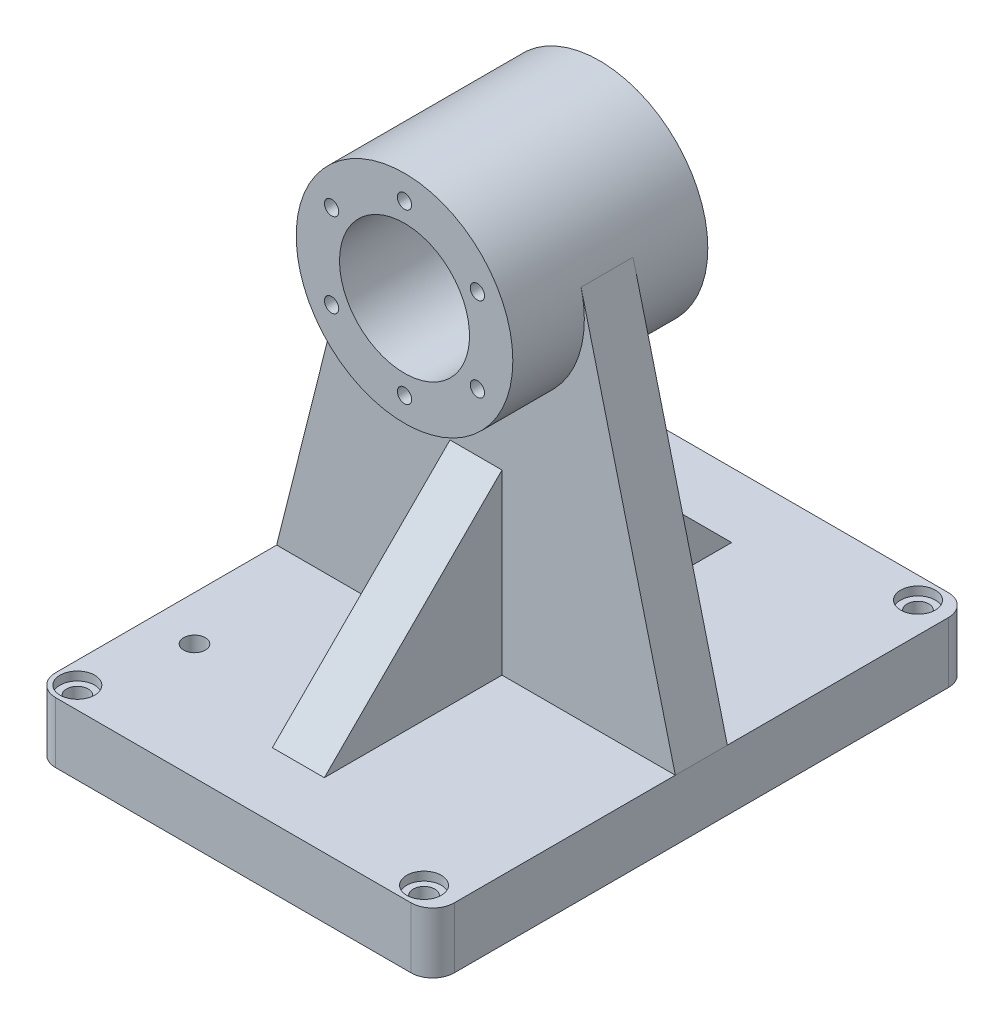
SolidWorks part; units mm, degrees
ref_plane "정면" through (0, 0, 0) normal (0, 0, 1) x (1, 0, 0)
ref_plane "윗면" through (0, 0, 0) normal (0, 1, 0) x (1, 0, 0)
ref_plane "우측면" through (0, 0, 0) normal (1, 0, 0) x (0, 0, -1)
sketch "스케치1" plane through (0, 0, 0) normal (0, 0, 1) x (1, 0, 0)
  circle A0 centre (0, 0.5754) radius 25
  circle A1 centre (0, 0.5754) radius 15
  point P3 (0, 0)
  dimension "D1" = 50
  dimension "D2" = 30
extrude "보스-돌출1" add sketch "스케치1" along normal mid plane 45
sketch "스케치2" plane through (0, 0, 0) normal (0, 0, 1) x (1, 0, 0)
  line L1 (-46, -80) -> (46, -80)
  line L2 (-46, -80) -> (-46, -94)
  line L3 (-46, -94) -> (46, -94)
  line L4 (46, -80) -> (46, -94)
  point P4 (0, -80)
  dimension "D1" = 14
  dimension "D2" = 92
  dimension "D3" = 80
extrude "보스-돌출2" add sketch "스케치2" along normal mid plane 124 separate body contours L1 L4 L3 L2
sketch "스케치4" plane through (0, 0, 0) normal (0, 0, 1) x (1, 0, 0)
  line L0 (-24.2478, 6.6616) -> (-46, -80)
  line L1 (-46, -80) -> (46, -80)
  line L2 (46, -80) -> (24.2478, 6.6616)
  circle A0 centre (0, 0.5754) radius 25 construction
  arc A1 (-24.2478, 6.6616) -> (24.2478, 6.6616) centre (0, 0.5754) ccw
extrude "보스-돌출3" add sketch "스케치4" along normal mid plane 12
sketch "스케치5" plane through (0, 0, 0) normal (1, 0, 0) x (0, 0, -1)
  line L0 (-47, -80) -> (-6, -39)
  line L1 (-62, -80) -> (-6, -80) construction
  line L2 (-6, -80) -> (-6, 6.6616) construction
  dimension "D1" = 15
  dimension "D2" = 45
rib "보강대1" sketch "스케치5" sketch "스케치5" thickness 12 extrusion direction parallel to sketch draft on no parameters "D1"=12
mirror "대칭 복사1" about plane through (0, 0, 0) normal (0, 0, 1) of "보강대1"
fillet "필렛1" radius 5 4 edges at (-46, -87, -62) (46, -87, -62) (46, -87, 62) (-46, -87, 62)
hole_wizard "M4 소켓 머리 캡 나사용 카운터보어2" positions "3D스케치2" profile "스케치9" counterbore size "M4" standard "KS" end condition through all
sketch3d "3D스케치2"
  line L0 (-41, -94, 57) -> (-41, -80, 57) construction
  point P0 (-41, -80, 57)
sketch "스케치9" plane through (-41, -80, 57) normal (1, 0, 0) x (0, 0, 1)
  line L0 (0, 0) -> (0, 14)
  line L1 (0, 14) -> (2.5, 14)
  line L3 (2.5, 14) -> (2.5, 2)
  line L4 (2.5, 2) -> (4, 2)
  line L5 (4, 2) -> (4, 0)
  line L7 (4, 0) -> (0, 0)
  line L11 (0, -6.35) -> (0, 107.95) construction
  dimension "관통 구멍 지름" = 5
  dimension "관통 구멍 깊이" = 14
  dimension "카운터보어 지름" = 8
  dimension "카운터보어 깊이" = 2
pattern_linear "선형 패턴1" count 2 spacing 80 along (1, 0, 0) count 2 spacing 114 along (0, 0, -1) of "M4 소켓 머리 캡 나사용 카운터보어2"
hole_wizard "M6 나사 구멍1" positions "3D스케치3" profile "스케치10" tap size "M6" standard "KS" end condition through all
sketch3d "3D스케치3"
  point P0 (-35.7233, -80, 35.2435)
sketch "스케치10" plane through (-35.7233, -80, 35.2435) normal (1, 0, 0) x (0, 0, 1)
  line L0 (0, 0) -> (0, 14)
  line L1 (0, 14) -> (2.5, 14)
  line L2 (2.5, 14) -> (2.5, 0)
  line L5 (2.5, 0) -> (0, 0)
  line L11 (0, -6.35) -> (0, 107.95) construction
  dimension "관통 탭 드릴 지름" = 5
  dimension "관통 탭 드릴 깊이" = 14
cosmetic thread "구멍 나사산1" parameters "D2"=6
sketch "스케치19" plane through (0, 0, 22.5) normal (0, 0, 1) x (1, 0, 0)
  point P0 (0, 20)
  dimension "D1" = 20
hole_wizard "M4 나사 구멍1" positions "3D스케치11" profile "스케치21" tap size "M4" standard "KS"
sketch3d "3D스케치11"
  point P0 (0, 20, 22.5)
sketch "스케치21" plane through (0, 20, 22.5) normal (1, 0, 0) x (0, -1, 0)
  line L0 (0, 0) -> (0, 12.4914)
  line L1 (0, 12.4914) -> (1.65, 11.5)
  line L2 (1.65, 11.5) -> (1.65, 0)
  line L5 (1.65, 0) -> (0, 0)
  line L10 (0, 12.4914) -> (-1.65, 11.5) construction
  line L11 (0, -6.35) -> (0, 107.95) construction
  dimension "탭 드릴 지름" = 3.3
  dimension "탭 드릴 깊이" = 11.5
  dimension "드릴 각도" = 118
cosmetic thread "구멍 나사산2" parameters "D1"=8, "D2"=4
pattern_circular "원형 패턴1" count 6 over 360 about axis through (0, 0.5754, 0) along (0, 0, 1) of "M4 나사 구멍1"
cosmetic thread "구멍 나사산3" parameters "D1"=8, "D2"=4
cosmetic thread "구멍 나사산4" parameters "D1"=8, "D2"=4
cosmetic thread "구멍 나사산5" parameters "D1"=8, "D2"=4
cosmetic thread "구멍 나사산6" parameters "D1"=8, "D2"=4
cosmetic thread "구멍 나사산7" parameters "D1"=8, "D2"=4
mirror "대칭 복사2" about plane through (0, 0, 0) normal (0, 0, 1) of "원형 패턴1", "M4 나사 구멍1"
cosmetic thread "구멍 나사산8" parameters "D1"=8, "D2"=4
cosmetic thread "구멍 나사산9" parameters "D1"=8, "D2"=4
cosmetic thread "구멍 나사산10" parameters "D1"=8, "D2"=4
cosmetic thread "구멍 나사산11" parameters "D1"=8, "D2"=4
cosmetic thread "구멍 나사산12" parameters "D1"=8, "D2"=4
cosmetic thread "구멍 나사산13" parameters "D1"=8, "D2"=4
